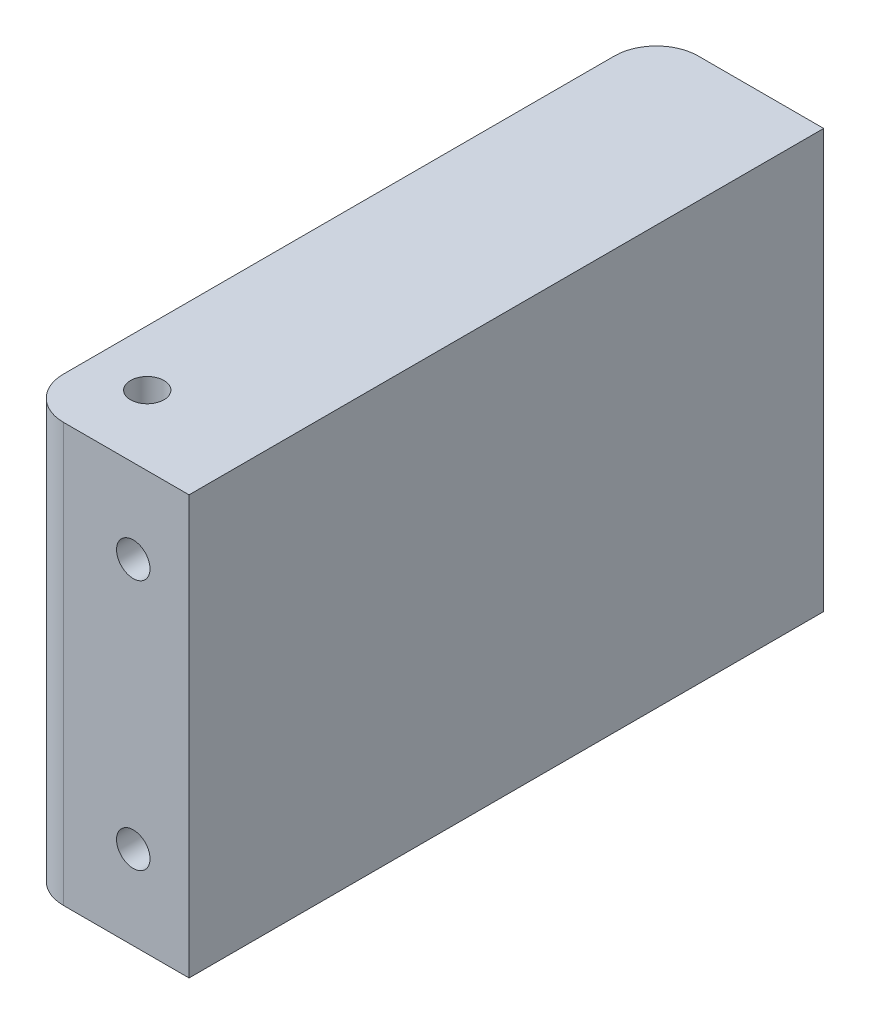
SolidWorks part; units mm, degrees
material "ABS"
ref_plane "Plan de face" through (0, 0, 0) normal (0, 0, 1) x (1, 0, 0)
ref_plane "Plan de dessus" through (0, 0, 0) normal (0, 1, 0) x (1, 0, 0)
ref_plane "Plan de droite" through (0, 0, 0) normal (1, 0, 0) x (0, 0, -1)
sketch "Esquisse1" plane through (0, 0, 0) normal (0, 1, 0) x (1, 0, 0)
  line L1 (-6, 45.5) -> (6, 45.5)
  line L2 (-6, 45.5) -> (-6, 0)
  line L3 (-6, 0) -> (6, 0)
  line L4 (6, 45.5) -> (6, 0)
  circle A0 centre (-2, 5) radius 1.2
  dimension "D3" = 2.4
  dimension "D4" = 4
  dimension "D5" = 5
  dimension "D1" = 12
  dimension "D2" = 45.5
extrude "Boss.-Extru.1" add sketch "Esquisse1" along normal mid plane 30
sketch "Esquisse2" plane through (0, 0, 0) normal (0, 0, 1) x (1, 0, 0)
  line L1 (-6, 0) -> (6, 0) construction
  line L2 (-6, 15) -> (-6, -15) construction
  line L3 (6, 15) -> (6, -15) construction
  circle A0 centre (2, 9) radius 1.2
  circle A1 centre (2, -9) radius 1.2
  dimension "D1" = 18
  dimension "D2" = 4
  dimension "D3" = 2.4
extrude "Enlèv. mat.-Extru.1" cut sketch "Esquisse2" against normal through all
fillet "Congé1" radius 3 2 edges at (-6, 0, -45.5) (-6, 0, 0)
